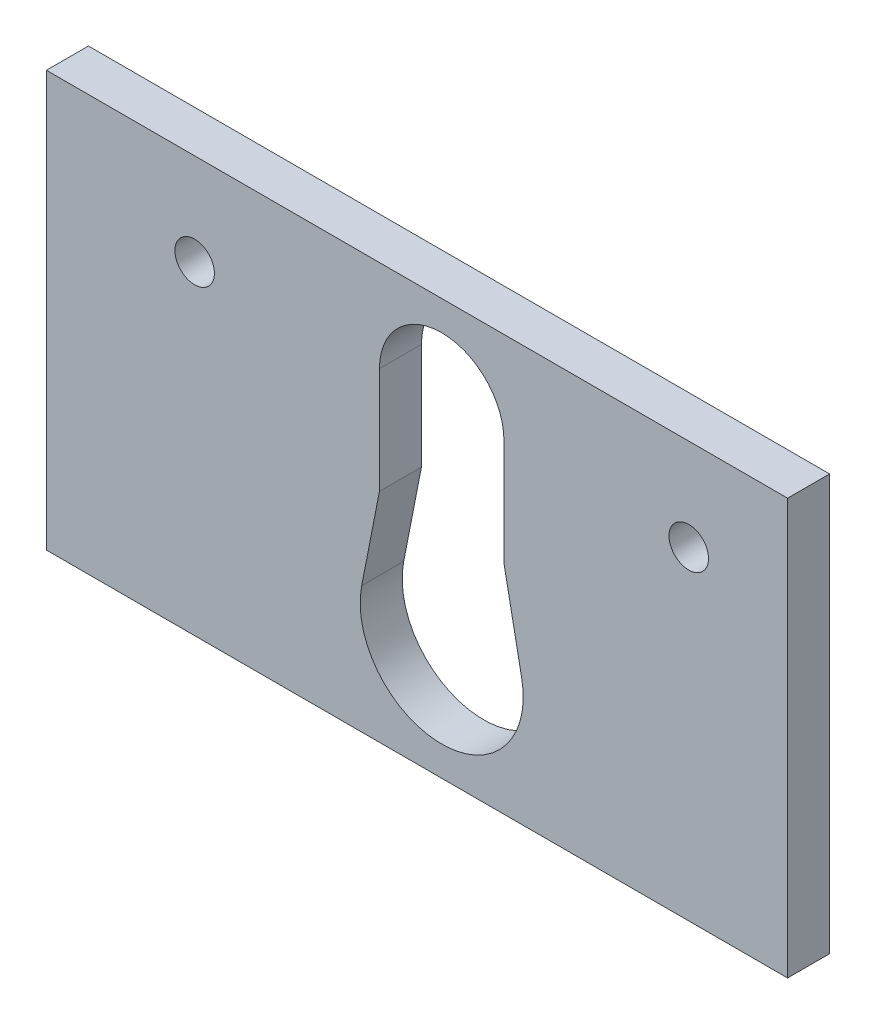
SolidWorks part; units mm, degrees
ref_plane "Front Plane" through (0, 0, 0) normal (0, 0, 1) x (1, 0, 0)
ref_plane "Top Plane" through (0, 0, 0) normal (0, 1, 0) x (1, 0, 0)
ref_plane "Right Plane" through (0, 0, 0) normal (1, 0, 0) x (0, 0, -1)
sketch "Sketch1" plane through (0, 0, 0) normal (0, 0, 1) x (1, 0, 0)
  line L0 (-10.75, -32.25) -> (10.75, -32.25) construction
  line L1 (-10.75, -10.75) -> (10.75, -10.75) construction
  line L2 (-10.75, -32.25) -> (-10.75, 10.75) construction
  line L3 (-10.75, 10.75) -> (10.75, 10.75) construction
  line L4 (10.75, -32.25) -> (10.75, 10.75) construction
  line L5 (-6.3, 0) -> (-6.3, -10.75)
  line L6 (6.3, 0) -> (6.3, -10.75)
  line L7 (-6.3, -10.75) -> (-8.096, -19.9132)
  line L8 (6.3, -10.75) -> (8.096, -19.9132)
  line L9 (-40, 0) -> (35, 0) construction
  line L10 (-10.75, -10.75) -> (-40, -10.75) construction
  line L11 (35, -32.75) -> (-40, -32.75)
  line L12 (35, -32.75) -> (35, 9.3)
  line L13 (35, 9.3) -> (-40, 9.3)
  line L14 (-40, -32.75) -> (-40, 9.3)
  line L15 (0, 6.3) -> (0, 9.3) construction
  line L16 (0, -29.75) -> (0, -32.75) construction
  circle A0 centre (0, 0) radius 6.3 construction
  circle A1 centre (0, 0) radius 8.25 construction
  circle A2 centre (0, 0) radius 10.75 construction
  circle A3 centre (0, -21.5) radius 10.75 construction
  circle A4 centre (0, -21.5) radius 8.25 construction
  circle A5 centre (0, -21.5) radius 6.3 construction
  arc A6 (6.3, 0) -> (-6.3, 0) centre (0, 0) ccw
  arc A7 (-8.096, -19.9132) -> (8.096, -19.9132) centre (0, -21.5) ccw
  circle A8 centre (25, 0) radius 2
  circle A9 centre (-25, 0) radius 2
  dimension "D1" = 12.6
  dimension "D2" = 16.5
  dimension "D3" = 21.5
  dimension "D5" = 4
  dimension "D4" = 3
  dimension "D8" = 4
  dimension "D6" = 75
  dimension "D7" = 3
  dimension "D9" = 25
  dimension "D10" = 25
  dimension "D11" = 10
extrude "Boss-Extrude2" add sketch "Sketch1" along normal blind 4.25 contours L14 L11 L12 L13 A9 A8 A7 L7 L5 A6 L6 L8
